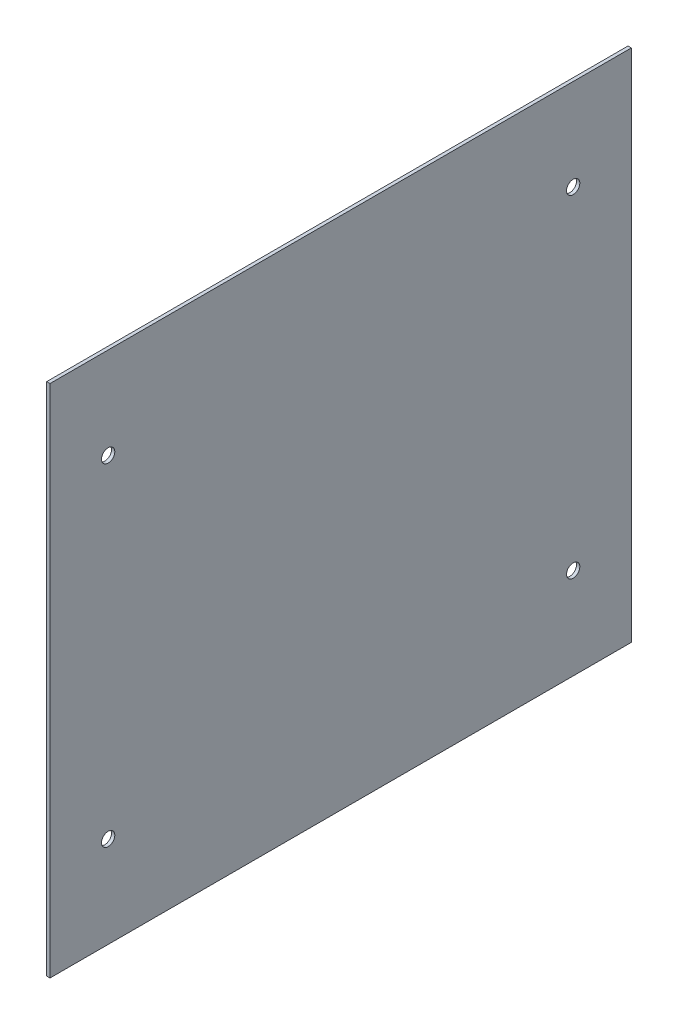
SolidWorks part; units mm, degrees
material "3003 Alloy"
ref_plane "Front Plane" through (0, 0, 0) normal (0, 0, 1) x (1, 0, 0)
ref_plane "Top Plane" through (0, 0, 0) normal (0, 1, 0) x (1, 0, 0)
ref_plane "Right Plane" through (0, 0, 0) normal (1, 0, 0) x (0, 0, -1)
sketch "Sketch1" plane through (0, 0, 0) normal (1, 0, 0) x (0, 0, -1)
  line L1 (175, -155) -> (-175, -155)
  line L2 (175, -155) -> (175, 155)
  line L3 (175, 155) -> (-175, 155)
  line L4 (-175, -155) -> (-175, 155)
  line L5 (175, -155) -> (-175, 155) construction
  line L6 (175, 155) -> (-175, -155) construction
  point P0 (0, 0)
  dimension "D1" = 350
  dimension "D2" = 310
extrude "Boss-Extrude1" add sketch "Sketch1" along normal blind 2
sketch "Sketch2" plane through (2, 0, 0) normal (1, 0, 0) x (0, 0, -1)
  line L0 (175, 155) -> (-175, 155) construction
  line L1 (-175, 155) -> (-175, -155) construction
  line L2 (0, 155) -> (0, -155) construction
  line L3 (-175, -155) -> (175, -155) construction
  line L4 (-175, 0) -> (175, 0) construction
  line L5 (175, -155) -> (175, 155) construction
  circle A0 centre (-140, 100) radius 4
  circle A1 centre (-140, -100) radius 4
  circle A2 centre (140, -100) radius 4
  circle A3 centre (140, 100) radius 4
  dimension "D1" = 8
  dimension "D2" = 55
  dimension "D3" = 35
extrude "Cut-Extrude1" cut sketch "Sketch2" against normal through all
